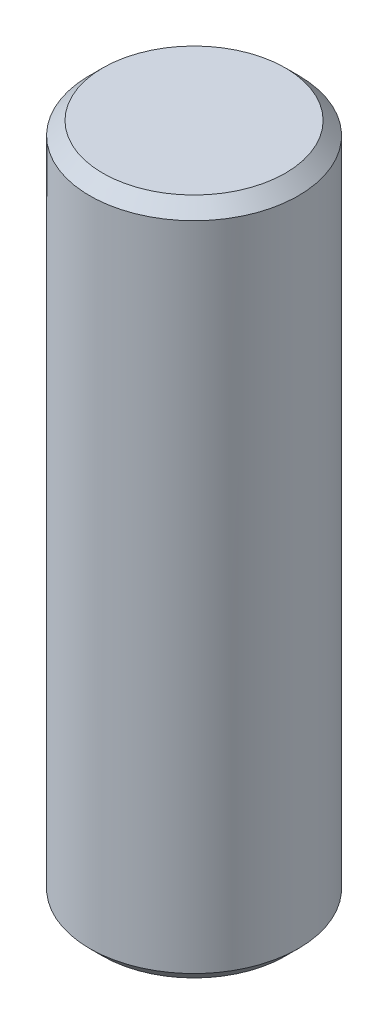
SolidWorks part; units mm, degrees
ref_plane "Front Plane" through (0, 0, 0) normal (0, 0, 1) x (1, 0, 0)
ref_plane "Top Plane" through (0, 0, 0) normal (0, 1, 0) x (1, 0, 0)
ref_plane "Right Plane" through (0, 0, 0) normal (1, 0, 0) x (0, 0, -1)
sketch "Sketch1" plane through (0, 0, 0) normal (0, 1, 0) x (1, 0, 0)
  circle A0 centre (0, 0) radius 8
  dimension "D1" = 16
extrude "Boss-Extrude1" add sketch "Sketch1" along normal mid plane 52
chamfer "Chamfer1" distance 1 angle 45 2 edges at (0, -26, 8) (0, 26, 8)
